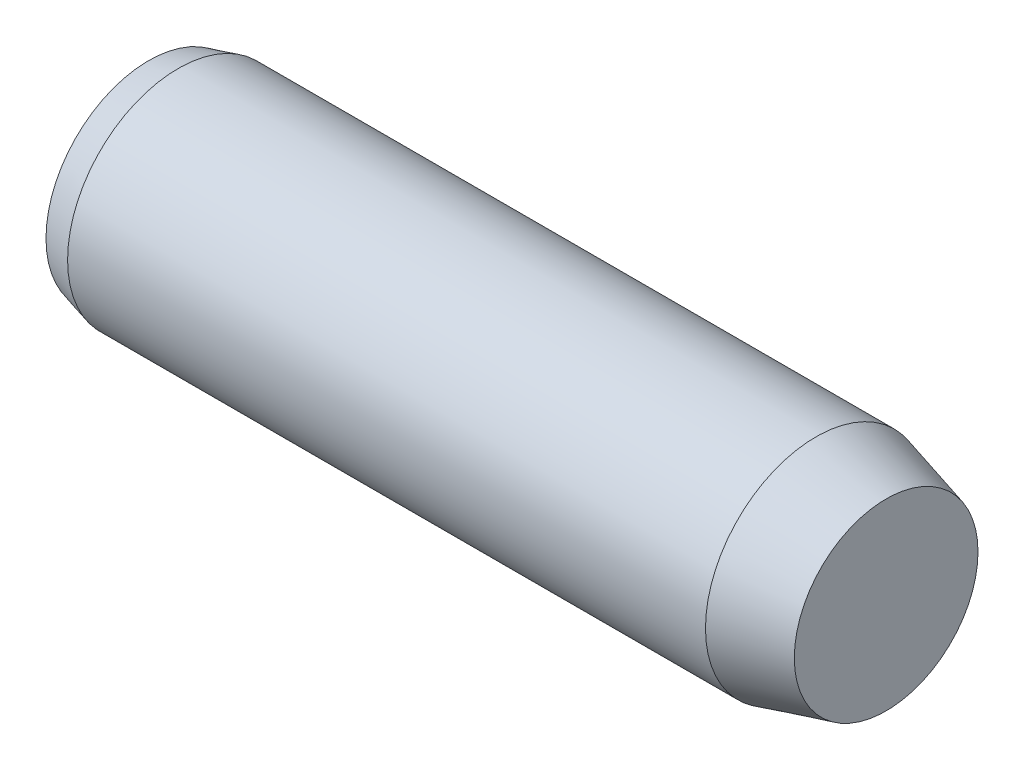
SolidWorks part; units mm, degrees
material "Stahl (gebürstet Nickel)"
ref_plane "Vorne" through (0, 0, 0) normal (0, 0, 1) x (1, 0, 0)
ref_plane "Oben" through (0, 0, 0) normal (0, 1, 0) x (1, 0, 0)
ref_plane "Rechts" through (0, 0, 0) normal (1, 0, 0) x (0, 0, -1)
sketch "Skizze1" plane through (0, 0, 0) normal (0, 0, 1) x (1, 0, 0)
  line L0 (0, 0) -> (0, 5.5713)
  line L1 (0, 5.5713) -> (1.6, 6)
  line L2 (1.6, 6) -> (36.2, 6)
  line L3 (36.2, 6) -> (40, 4.9818)
  line L4 (40, 4.9818) -> (40, 0)
  line L5 (0, 0) -> (40, 0) construction
  line L6 (0, 0) -> (40, 0)
  dimension "D1" = 12
  dimension "D2" = 40
  dimension "D3" = 1.6
  dimension "D4" = 3.8
  dimension "D5" = 15
  dimension "D6" = 15
revolve "Rotation3" add sketch "Skizze1" angle 360 about L5
hole_wizard "M6 Gewindebohrung1" positions "Skizze4" profile "Skizze5" tap size "M6" standard "Gabler-Normteile"
sketch "Skizze4" plane through (0, 0, 0) normal (-1, 0, 0) x (0, 0, 1)
  point P0 (0, 0)
cosmetic thread "Bohrungsgewinde1" parameters "D1"=10, "D2"=6
sketch "Skizze5" plane through (0, 0, 0) normal (0, 1, 0) x (0, 0, 1)
  line L0 (0, 0) -> (0, 16.5022)
  line L1 (0, 16.5022) -> (2.5, 15)
  line L2 (2.5, 15) -> (2.5, 0.525)
  line L3 (2.5, 0.525) -> (3.025, 0)
  line L5 (3.025, 0) -> (0, 0)
  line L6 (-2.5, 0.525) -> (-3.025, 0) construction
  line L10 (0, 16.5022) -> (-2.5, 15) construction
  line L11 (0, -6.35) -> (0, 107.95) construction
  dimension "Bohrerdurchmesser" = 5
  dimension "Bohrungstiefe" = 15
  dimension "Senkdurchmesser (Oben)" = 6.05
  dimension "Senkwinkel (Oben)" = 90
  dimension "Spitzenwinkel" = 118
